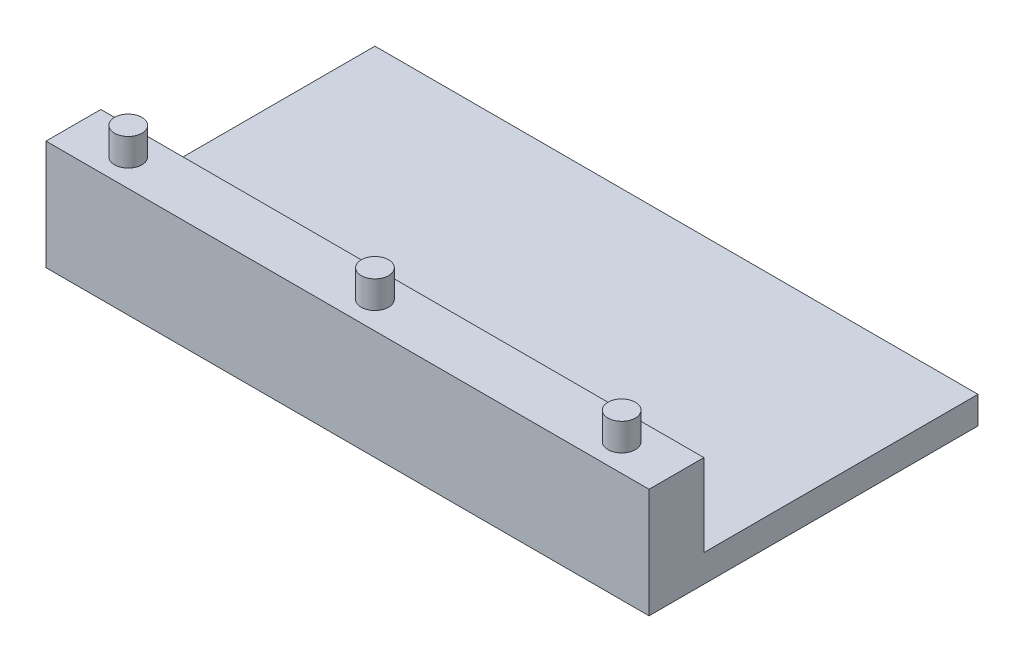
SolidWorks part; units mm, degrees
ref_plane "Front Plane" through (0, 0, 0) normal (0, 0, 1) x (1, 0, 0)
ref_plane "Top Plane" through (0, 0, 0) normal (0, 1, 0) x (1, 0, 0)
ref_plane "Right Plane" through (0, 0, 0) normal (1, 0, 0) x (0, 0, -1)
sketch "Sketch1" plane through (0, 0, 0) normal (0, 1, 0) x (1, 0, 0)
  line L0 (-69.85, -38.1) -> (69.85, -38.1)
  line L1 (-69.85, -38.1) -> (-69.85, 38.1)
  line L2 (69.85, -38.1) -> (69.85, 38.1)
  line L3 (-69.85, 38.1) -> (69.85, 38.1)
  line L4 (-69.85, -38.1) -> (69.85, 38.1) construction
  line L5 (69.85, -38.1) -> (-69.85, 38.1) construction
  point P1 (0, 0)
  dimension "D1" = 76.2
  dimension "D2" = 139.7
extrude "Boss-Extrude1" add sketch "Sketch1" along normal blind 6.35
sketch "Sketch2" plane through (0, 6.35, 0) normal (0, 1, 0) x (1, 0, 0)
  line L0 (-69.85, 38.1) -> (-69.85, -38.1) construction
  line L1 (-69.85, -38.1) -> (69.85, -38.1)
  line L2 (69.85, -38.1) -> (69.85, -25.4)
  line L3 (69.85, -38.1) -> (69.85, 38.1) construction
  line L4 (69.85, -25.4) -> (-69.85, -25.4)
  line L5 (-69.85, -25.4) -> (-69.85, -38.1)
  dimension "D2" = 12.7
extrude "Boss-Extrude2" add sketch "Sketch2" along normal blind 19.05
sketch "Sketch3" plane through (0, 6.35, 0) normal (0, 1, 0) x (1, 0, 0)
  line L1 (-69.85, -38.1) -> (69.85, -38.1) construction
  line L2 (-69.85, 38.1) -> (-69.85, -25.4) construction
  circle A0 centre (-53.34, -21.59) radius 2.032
  dimension "D1" = 4.064
  dimension "D2" = 16.51
  dimension "D3" = 16.51
extrude "Cut-Extrude1" cut sketch "Sketch3" against normal through all
sketch "Sketch4" plane through (0, 0, 0) normal (0, -1, 0) x (1, 0, 0)
  line L0 (-69.85, 38.1) -> (69.85, 38.1) construction
  line L1 (-50.927, 25.7694) -> (-55.753, 25.7694)
  line L2 (-55.753, 25.7694) -> (-58.166, 21.59)
  line L3 (-58.166, 21.59) -> (-55.753, 17.4106)
  line L4 (-55.753, 17.4106) -> (-50.927, 17.4106)
  line L5 (-50.927, 17.4106) -> (-48.514, 21.59)
  line L6 (-48.514, 21.59) -> (-50.927, 25.7694)
  circle A0 centre (-53.34, 21.59) radius 4.1794 construction
  dimension "D1" = 4.826
extrude "Cut-Extrude2" cut sketch "Sketch4" against normal blind 3.048
sketch "Sketch5" plane through (0, 25.4, 0) normal (0, 1, 0) x (1, 0, 0)
  line L0 (-69.85, -25.4) -> (-69.85, -38.1) construction
  line L3 (69.85, -25.4) -> (-69.85, -25.4) construction
  circle A0 centre (-57.15, -31.75) radius 3.175
  circle A1 centre (0, -31.75) radius 3.175
  circle A2 centre (57.15, -31.75) radius 3.175
  point P5 (-69.85, -31.75)
  dimension "D2" = 6.35
  dimension "D1" = 12.7
  dimension "D4" = 57.15
  dimension "D5" = 6.35
  dimension "D3" = 3
extrude "Boss-Extrude3" add sketch "Sketch5" along normal blind 6.35
